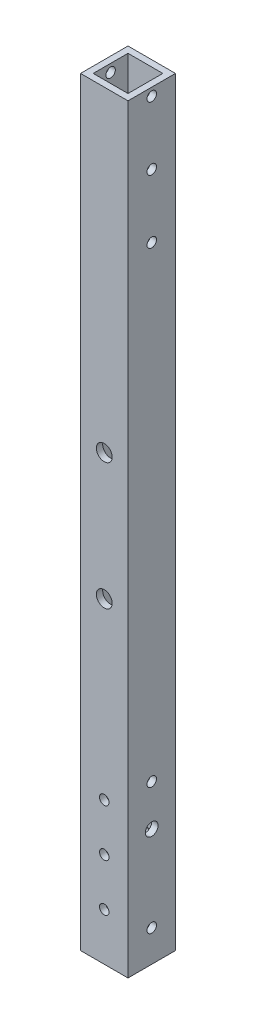
SolidWorks part; units mm, degrees
material "6061 合金"
ref_plane "前视基准面" through (0, 0, 0) normal (0, 0, 1) x (1, 0, 0)
ref_plane "上视基准面" through (0, 0, 0) normal (0, 1, 0) x (1, 0, 0)
ref_plane "右视基准面" through (0, 0, 0) normal (1, 0, 0) x (0, 0, -1)
sketch "草图1" plane through (0, 0, 0) normal (0, 1, 0) x (1, 0, 0)
  line L1 (-7.5, 7.5) -> (7.5, 7.5)
  line L2 (-7.5, 7.5) -> (-7.5, -7.5)
  line L3 (-7.5, -7.5) -> (7.5, -7.5)
  line L4 (7.5, 7.5) -> (7.5, -7.5)
  line L5 (-7.5, 7.5) -> (7.5, -7.5) construction
  line L6 (-7.5, -7.5) -> (7.5, 7.5) construction
  point P0 (0, 0)
extrude "凸台-拉伸1" add sketch "草图1" along normal blind 240
sketch "草图2" plane through (0, 240, 0) normal (0, 1, 0) x (1, 0, 0)
  line L1 (-5.5, 5.5) -> (5.5, 5.5)
  line L2 (-5.5, 5.5) -> (-5.5, -5.5)
  line L3 (-5.5, -5.5) -> (5.5, -5.5)
  line L4 (5.5, 5.5) -> (5.5, -5.5)
  line L5 (-5.5, 5.5) -> (5.5, -5.5) construction
  line L6 (-5.5, -5.5) -> (5.5, 5.5) construction
  point P0 (0, 0)
extrude "切除-拉伸1" cut sketch "草图2" against normal blind 240
sketch "草图3" plane through (0, 0, 7.5) normal (0, 0, 1) x (1, 0, 0)
  line L0 (7.5, 240) -> (7.5, 0) construction
  line L1 (-7.5, 240) -> (7.5, 240) construction
  line L2 (-7.5, 0) -> (7.5, 0) construction
  circle A0 centre (0, 50) radius 2.5
  circle A1 centre (0, 100) radius 2.5
  circle A2 centre (0, 140) radius 2.5
  circle A3 centre (0, 190) radius 2.5
  dimension "D1" = 7.5
  dimension "D2" = 5
  dimension "D3" = 5
  dimension "D4" = 5
  dimension "D5" = 5
  dimension "D6" = 50
  dimension "D7" = 50
  dimension "D8" = 7.5
  dimension "D9" = 7.5
  dimension "D10" = 7.5
  dimension "D11" = 50
  dimension "D12" = 50
extrude "切除-拉伸2" cut sketch "草图3" against normal blind 15 contours A2 | A1
sketch "草图4" plane through (0, 0, 7.5) normal (0, 0, 1) x (1, 0, 0)
  line L0 (-7.5, 0) -> (7.5, 0) construction
  line L1 (7.5, 240) -> (7.5, 0) construction
  circle A0 centre (0, 45) radius 1.5
  circle A1 centre (0, 30) radius 1.5
  circle A2 centre (0, 15) radius 1.5
  dimension "D1" = 15
  dimension "D5" = 3
  dimension "D6" = 3
  dimension "D7" = 3
  dimension "D2" = 15
  dimension "D3" = 15
  dimension "D4" = 7.5
extrude "切除-拉伸3" cut sketch "草图4" against normal blind 15
sketch "草图5" plane through (-7.5, 0, 0) normal (-1, 0, 0) x (0, 0, 1)
  line L0 (7.5, 240) -> (7.5, 0) construction
  line L1 (-7.5, 0) -> (7.5, 0) construction
  line L2 (-7.5, 240) -> (7.5, 240) construction
  circle A0 centre (0, 10) radius 1.5
  circle A1 centre (0, 37) radius 2
  circle A2 centre (0, 50) radius 1.5
  circle A3 centre (0, 237.5) radius 1.5
  circle A4 centre (0, 217.5) radius 1.5
  circle A5 centre (0, 197.5) radius 1.5
  dimension "D1" = 3
  dimension "D4" = 2.5
  dimension "D2" = 7.5
  dimension "D3" = 10
  dimension "D5" = 20
  dimension "D6" = 20
  dimension "D7" = 27
  dimension "D8" = 13
extrude "切除-拉伸4" cut sketch "草图5" against normal blind 15
